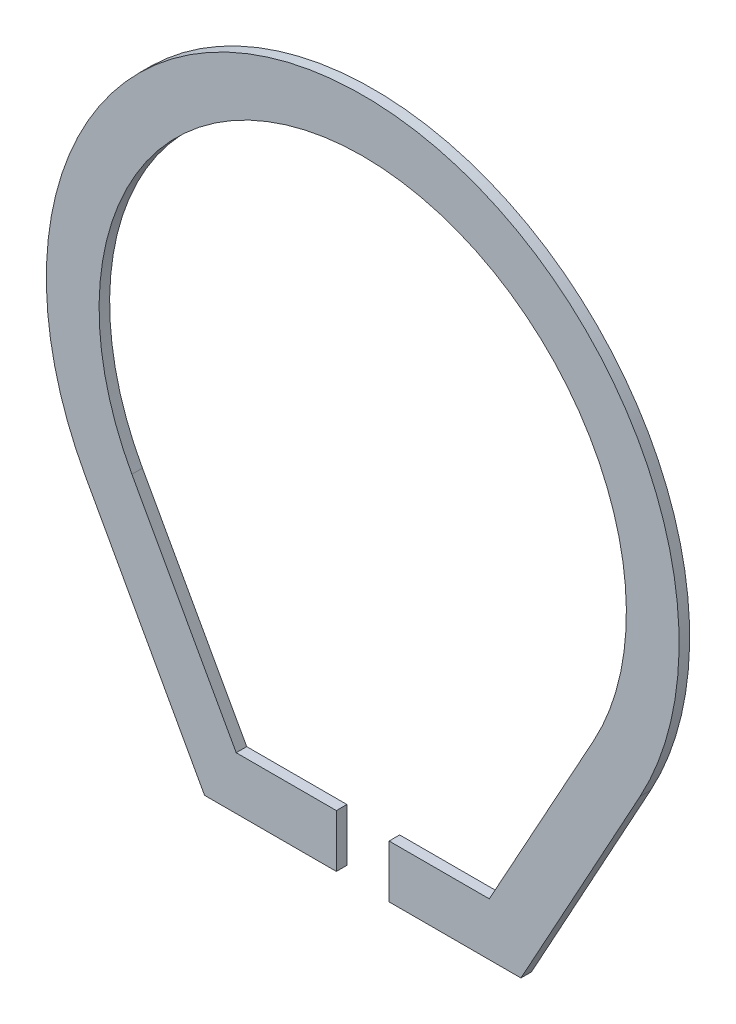
SolidWorks part; units mm, degrees
ref_plane "Plano frontal" through (0, 0, 0) normal (0, 0, 1) x (1, 0, 0)
ref_plane "Plano superior" through (0, 0, 0) normal (0, 1, 0) x (1, 0, 0)
ref_plane "Plano direito" through (0, 0, 0) normal (1, 0, 0) x (0, 0, -1)
sketch "Esboço1" plane through (0, 0, 0) normal (0, 0, 1) x (1, 0, 0)
  line L0 (5, -35) -> (15, -35)
  line L1 (-15, -35) -> (-5, -35)
  line L2 (15, -35) -> (26.2929, -14.4459)
  line L3 (-15, -35) -> (-26.2929, -14.4459)
  line L4 (-12, -30) -> (-5, -30)
  line L5 (-12, -30) -> (-21.889, -12.0777)
  line L6 (12, -30) -> (21.889, -12.0777)
  line L9 (5, -30) -> (12, -30)
  line L10 (-5, -30) -> (-2.5, -30)
  line L11 (-2.5, -32.5) -> (-2.5, -35)
  line L12 (-2.5, -35) -> (-5, -35)
  line L13 (2.5, -32.5) -> (2.5, -35)
  line L14 (2.5, -35) -> (5, -35)
  line L15 (-2.5, -32.5) -> (-2.5, -30)
  line L16 (2.5, -32.5) -> (2.5, -30)
  line L17 (2.5, -30) -> (5, -30)
  arc A0 (26.2929, -14.4459) -> (-26.2929, -14.4459) centre (0, 0) ccw
  arc A1 (21.889, -12.0777) -> (-21.889, -12.0777) centre (0, 0) ccw
  point P5 (0, -30)
  point P8 (0, -35)
  point P13 (0, -30)
  dimension "D1" = 60
  dimension "D2" = 50
  dimension "D8" = 2.5
  dimension "D3" = 30
  dimension "D4" = 24
  dimension "D5" = 10
  dimension "D6" = 5
  dimension "D7" = 5
extrude "Ressalto-extrusão3" add sketch "Esboço1" along normal blind 1
